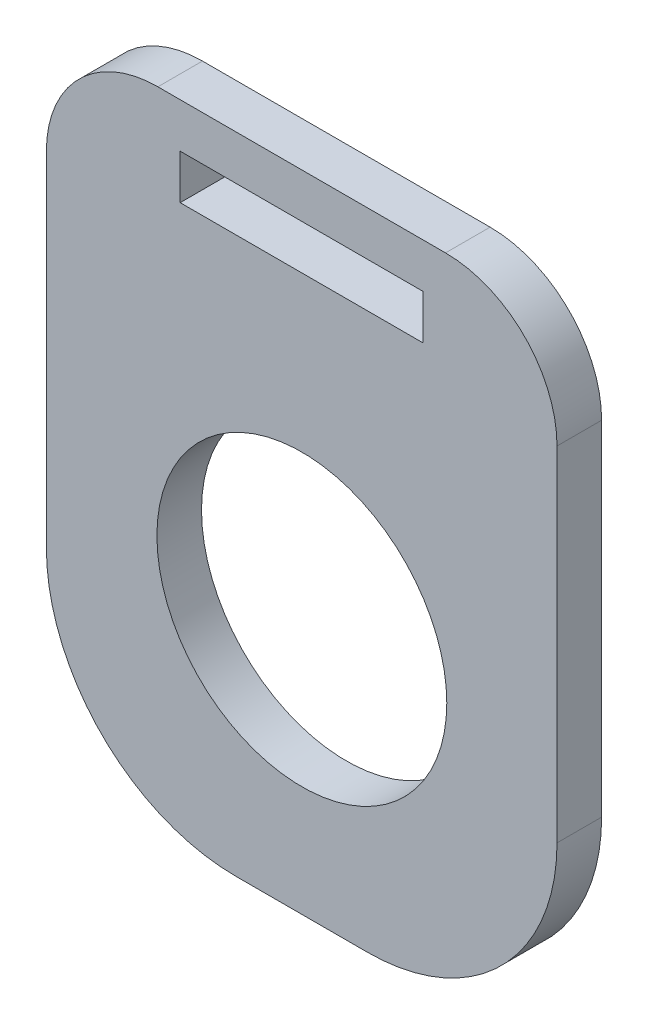
SolidWorks part; units mm, degrees
ref_plane "Front Plane" through (0, 0, 0) normal (0, 0, 1) x (1, 0, 0)
ref_plane "Top Plane" through (0, 0, 0) normal (0, 1, 0) x (1, 0, 0)
ref_plane "Right Plane" through (0, 0, 0) normal (1, 0, 0) x (0, 0, -1)
sketch "Sketch1" plane through (0, 0, 0) normal (0, 0, 1) x (1, 0, 0)
  line L1 (0, 0) -> (58.166, 0)
  line L2 (0, 0) -> (0, 73.44)
  line L3 (0, 73.44) -> (58.166, 73.44)
  line L4 (58.166, 0) -> (58.166, 73.44)
  dimension "D1" = 73.44
  dimension "D2" = 58.166
extrude "Boss-Extrude1" add sketch "Sketch1" along normal blind 5.08
sketch "Sketch2" plane through (0, 0, 5.08) normal (0, 0, 1) x (1, 0, 0)
  line L0 (0, 58.2) -> (58.166, 58.2) construction
  line L1 (0, 73.44) -> (0, 0) construction
  line L2 (58.166, 0) -> (58.166, 73.44) construction
  line L4 (15.24, 68.36) -> (42.926, 68.36)
  line L5 (15.24, 68.36) -> (15.24, 63.28)
  line L6 (15.24, 63.28) -> (42.926, 63.28)
  line L7 (42.926, 68.36) -> (42.926, 63.28)
  line L8 (0, 65.82) -> (15.24, 65.82) construction
  line L9 (42.926, 65.82) -> (58.166, 65.82) construction
  dimension "D1" = 15.24
  dimension "D2" = 5.08
  dimension "D4" = 5.08
  dimension "D3" = 15.24
  dimension "D5" = 27.686
sketch "Sketch4" plane through (0, 0, 5.08) normal (0, 0, 1) x (1, 0, 0)
extrude "Cut-Extrude1" cut sketch "Sketch2" against normal through all
sketch "Sketch7" plane through (0, 0, 5.08) normal (0, 0, 1) x (1, 0, 0)
  line L0 (0, 0) -> (58.166, 0) construction
  line L1 (0, 73.44) -> (0, 0) construction
  circle A0 centre (29.1, 29.1) radius 16.51
  dimension "D1" = 33.02
  dimension "D2" = 29.1
  dimension "D3" = 29.1
extrude "Cut-Extrude2" cut sketch "Sketch7" against normal through all and the other way through all
fillet "Fillet2" radius 21.59 2 edges at (58.166, 0, 2.54) (0, 0, 2.54)
fillet "Fillet3" radius 12.7 2 edges at (0, 73.44, 2.54) (58.166, 73.44, 2.54)
equation "\"MDF\"= .2"
equation "\"Foamcore\"= .1"
equation "\"GMaterial\"= \"MDF\""
equation "\"CutDistance\" = .1"
equation "\"D1@Boss-Extrude1\"=\"GMaterial\""
equation "\"D1@Sketch1\"=3*\"GMaterial\" + 58.2mm"
equation "\"D1@Sketch2\"=3*\"GMaterial\""
equation "\"D2@Sketch2\"=\"GMaterial\""
equation "\"D4@Sketch2\"=\"GMaterial\""
